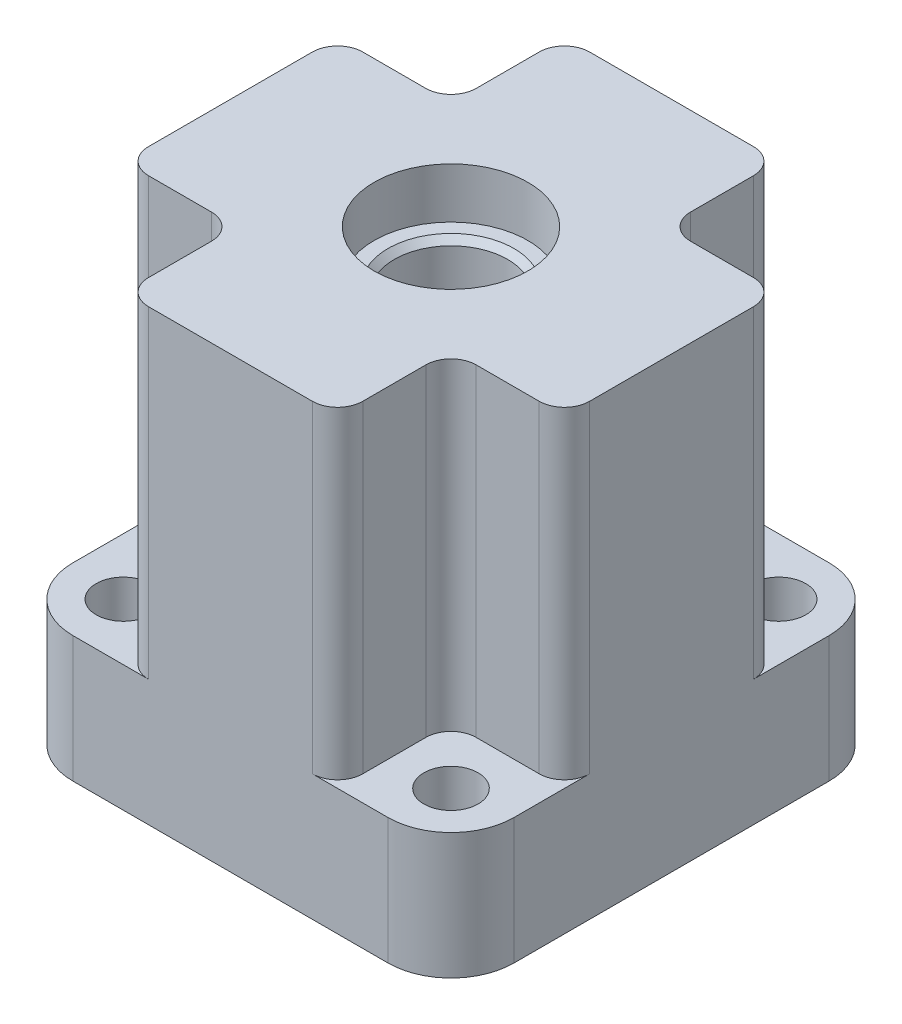
SolidWorks part; units mm, degrees
ref_plane "前视基准面" through (0, 0, 0) normal (0, 0, 1) x (1, 0, 0)
ref_plane "上视基准面" through (0, 0, 0) normal (0, 1, 0) x (1, 0, 0)
ref_plane "右视基准面" through (0, 0, 0) normal (1, 0, 0) x (0, 0, -1)
sketch "草图1" plane through (0, 0, 0) normal (0, 1, 0) x (1, 0, 0)
  line L1 (-17.5, -17.5) -> (17.5, -17.5)
  line L2 (-17.5, -17.5) -> (-17.5, 17.5)
  line L3 (-17.5, 17.5) -> (17.5, 17.5)
  line L4 (17.5, -17.5) -> (17.5, 17.5)
  line L5 (-17.5, -17.5) -> (17.5, 17.5) construction
  line L6 (-17.5, 17.5) -> (17.5, -17.5) construction
  line L7 (-13, -13) -> (13, -13) construction
  line L8 (-13, -13) -> (-13, 13) construction
  line L9 (-13, 13) -> (13, 13) construction
  line L10 (13, -13) -> (13, 13) construction
  line L11 (-13, -13) -> (13, 13) construction
  line L12 (-13, 13) -> (13, -13) construction
  circle A0 centre (0, 0) radius 4.5
  circle A1 centre (13, 13) radius 2.15
  circle A2 centre (13, -13) radius 2.15
  circle A3 centre (-13, -13) radius 2.15
  circle A4 centre (-13, 13) radius 2.15
  circle A5 centre (13, 13) radius 4 construction
  point P0 (0, 0)
  point P22 (0, 0)
  dimension "D1" = 9
  dimension "D6" = 4.3
  dimension "D7" = 4
  dimension "D8" = 8
  dimension "D2" = 35
  dimension "D3" = 35
  dimension "D4" = 26
  dimension "D5" = 26
extrude "凸台-拉伸1" add sketch "草图1" along normal blind 25
fillet "圆角1" radius 5 4 edges at (17.5, 12.5, -17.5) (17.5, 12.5, 17.5) (-17.5, 12.5, 17.5) (-17.5, 12.5, -17.5)
sketch "草图2" plane through (0, 25, 0) normal (0, 1, 0) x (1, 0, 0)
  circle A0 centre (0, 0) radius 6.1 construction
  circle A1 centre (-13, 13) radius 4 construction
  circle A2 centre (0, 0) radius 6.8 construction
  dimension "D1" = 12.2
  dimension "D2" = 8
  dimension "D3" = 13.6
sketch "草图3" plane through (0, 25, 0) normal (0, 1, 0) x (1, 0, 0)
  circle A0 centre (0, 0) radius 6.1 construction
  circle A1 centre (0, 0) radius 6.1
extrude "切除-拉伸1" cut sketch "草图3" against normal blind 4
ref_plane "基准面1" through (0, 13, 0) normal (0, 1, 0) x (1, 0, 0)
sketch "草图4" plane through (0, 13, 0) normal (0, 1, 0) x (1, 0, 0)
  circle A0 centre (0, 0) radius 6.1
  dimension "D1" = 12.2
extrude "切除-拉伸2" cut sketch "草图4" against normal blind 4
sketch "草图6" plane through (0, 0, 0) normal (0, -1, 0) x (1, 0, 0)
  circle A0 centre (0, 0) radius 10
  dimension "D1" = 20
extrude "切除-拉伸3" cut sketch "草图6" against normal blind 9
sketch "草图7" plane through (0, 0, 0) normal (0, -1, 0) x (1, 0, 0)
  line L4 (-12.5, -17.5) -> (12.5, -17.5)
  line L5 (17.5, -12.5) -> (17.5, 12.5)
  line L6 (12.5, 17.5) -> (-12.5, 17.5)
  line L7 (-17.5, 12.5) -> (-17.5, -12.5)
  line L8 (-12.5, -17.5) -> (12.5, -17.5)
  line L9 (17.5, -12.5) -> (17.5, 12.5)
  line L10 (12.5, 17.5) -> (-12.5, 17.5)
  line L11 (-17.5, 12.5) -> (-17.5, -12.5)
  circle A0 centre (-13, -13) radius 2.15 construction
  circle A1 centre (-13, 13) radius 2.15 construction
  circle A2 centre (0, 0) radius 10 construction
  circle A3 centre (13, -13) radius 2.15 construction
  arc A4 (12.5, -17.5) -> (17.5, -12.5) centre (12.5, -12.5) ccw
  arc A5 (17.5, 12.5) -> (12.5, 17.5) centre (12.5, 12.5) ccw
  arc A6 (-12.5, 17.5) -> (-17.5, 12.5) centre (-12.5, 12.5) ccw
  arc A7 (-17.5, -12.5) -> (-12.5, -17.5) centre (-12.5, -12.5) ccw
  arc A8 (12.5, -17.5) -> (17.5, -12.5) centre (12.5, -12.5) ccw
  arc A9 (17.5, 12.5) -> (12.5, 17.5) centre (12.5, 12.5) ccw
  arc A10 (-12.5, 17.5) -> (-17.5, 12.5) centre (-12.5, 12.5) ccw
  arc A11 (-17.5, -12.5) -> (-12.5, -17.5) centre (-12.5, -12.5) ccw
  circle A12 centre (13, 13) radius 2.15 construction
  circle A13 centre (-13, -13) radius 2.15
  circle A14 centre (-13, 13) radius 2.15
  circle A15 centre (0, 0) radius 10
  circle A16 centre (13, -13) radius 2.15
  circle A17 centre (13, 13) radius 2.15
  dimension "D1" = 0
extrude "凸台-拉伸2" add sketch "草图7" along normal blind 10.6
sketch "草图8" plane through (0, 25, 0) normal (0, 1, 0) x (1, 0, 0)
  line L0 (-17.5, 12.5) -> (-17.5, -12.5) construction
  line L1 (-8.5, 8.5) -> (-17.5, 8.5)
  line L2 (-8.5, 8.5) -> (-8.5, 17.5)
  line L3 (-8.5, 17.5) -> (-17.5, 17.5)
  line L4 (-17.5, 8.5) -> (-17.5, 17.5)
  line L5 (-8.5, 8.5) -> (-17.5, 17.5) construction
  line L6 (-8.5, 17.5) -> (-17.5, 8.5) construction
  line L7 (12.5, 17.5) -> (-12.5, 17.5) construction
  line L8 (8.5, 8.5) -> (17.5, 8.5)
  line L9 (8.5, 8.5) -> (8.5, 17.5)
  line L10 (8.5, 17.5) -> (17.5, 17.5)
  line L11 (17.5, 8.5) -> (17.5, 17.5)
  line L12 (8.5, -8.5) -> (8.5, -17.5)
  line L13 (8.5, -8.5) -> (17.5, -8.5)
  line L14 (17.5, -8.5) -> (17.5, -17.5)
  line L15 (8.5, -17.5) -> (17.5, -17.5)
  line L16 (-8.5, -8.5) -> (-17.5, -8.5)
  line L17 (-8.5, -8.5) -> (-8.5, -17.5)
  line L18 (-8.5, -17.5) -> (-17.5, -17.5)
  line L19 (-17.5, -8.5) -> (-17.5, -17.5)
  point P0 (-13, 13)
  point P25 (0, 0)
  dimension "D1" = 0
  dimension "D2" = 0
  dimension "D3" = 4
extrude "切除-拉伸4" cut sketch "草图8" against normal blind 25.6
fillet "圆角2" radius 2 12 edges at (-17.5, 12.2, -8.5) (-8.5, 12.2, -8.5) (-8.5, 12.2, -17.5) (8.5, 12.2, -17.5) (8.5, 12.2, -8.5) (17.5, 12.2, -8.5) (17.5, 12.2, 8.5) (8.5, 12.2, 8.5) (8.5, 12.2, 17.5) (-8.5, 12.2, 17.5) (-8.5, 12.2, 8.5) (-17.5, 12.2, 8.5)
chamfer "倒角1" distance 1 angle 45 1 edges at (0, -10.6, -10)
chamfer "倒角2" distance 0.5 angle 45 2 edges at (0, 13, 4.5) (0, 21, 4.5)
